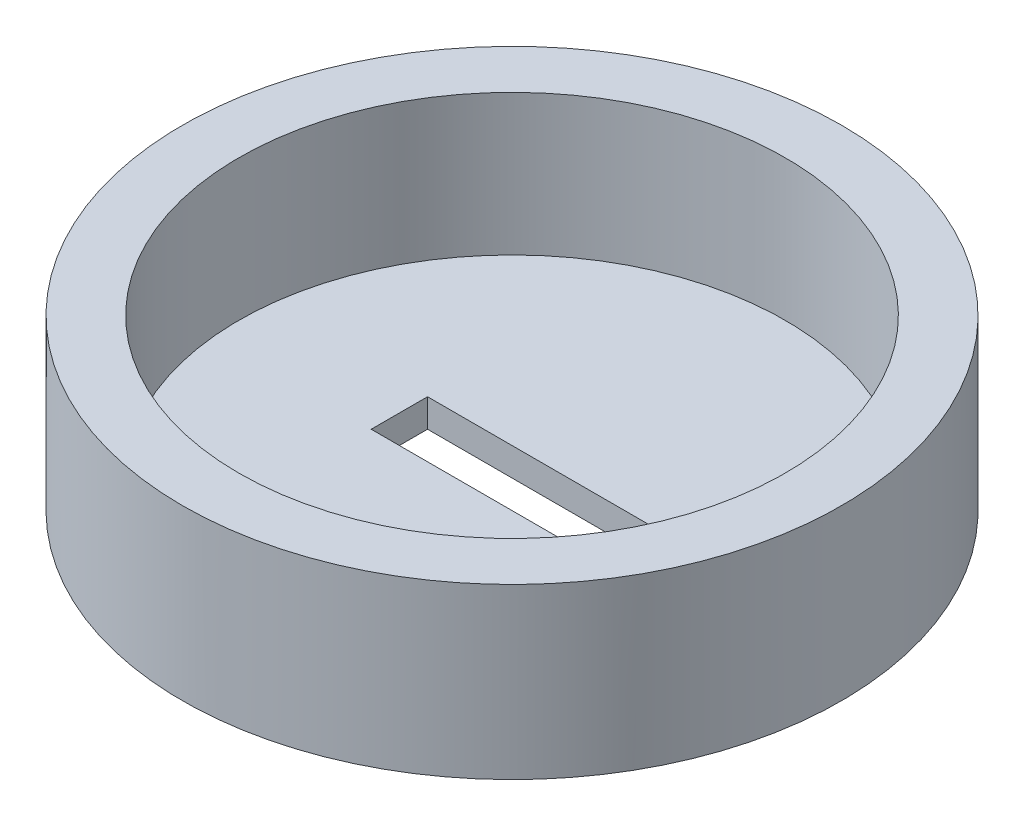
SolidWorks part; units mm, degrees
ref_plane "Front Plane" through (0, 0, 0) normal (0, 0, 1) x (1, 0, 0)
ref_plane "Top Plane" through (0, 0, 0) normal (0, 1, 0) x (1, 0, 0)
ref_plane "Right Plane" through (0, 0, 0) normal (1, 0, 0) x (0, 0, -1)
sketch "Sketch1" plane through (0, 0, 0) normal (0, 1, 0) x (1, 0, 0)
  circle A0 centre (0, 0) radius 9.7
  circle A1 centre (0, 0) radius 11.7
  dimension "D1" = 19.4
  dimension "D2" = 2
extrude "Boss-Extrude1" add sketch "Sketch1" along normal blind 5
sketch "Sketch2" plane through (0, 0, 0) normal (0, -1, 0) x (1, 0, 0)
  circle A1 centre (0, 0) radius 11.7
  circle A2 centre (0, 0) radius 11.7
  dimension "D1" = 0
extrude "Boss-Extrude2" add sketch "Sketch2" along normal blind 1
sketch "Sketch3" plane through (0, -1, 0) normal (0, -1, 0) x (1, 0, 0)
  line L1 (-4, 1) -> (4, 1)
  line L2 (-4, 1) -> (-4, -1)
  line L3 (-4, -1) -> (4, -1)
  line L4 (4, 1) -> (4, -1)
  line L5 (-4, 1) -> (4, -1) construction
  line L6 (-4, -1) -> (4, 1) construction
  point P0 (0, 0)
  dimension "D1" = 2
  dimension "D2" = 8
extrude "Cut-Extrude1" cut sketch "Sketch3" against normal blind 7
